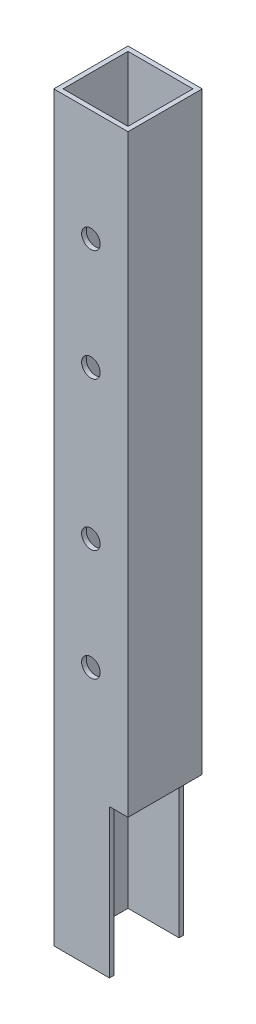
SolidWorks part; units mm, degrees
ref_plane "Front Plane" through (0, 0, 0) normal (0, 0, 1) x (1, 0, 0)
ref_plane "Top Plane" through (0, 0, 0) normal (0, 1, 0) x (1, 0, 0)
ref_plane "Right Plane" through (0, 0, 0) normal (1, 0, 0) x (0, 0, -1)
sketch "Sketch1" plane through (0, 0, 0) normal (0, 1, 0) x (1, 0, 0)
  line L1 (-12.7, 12.7) -> (12.7, 12.7)
  line L2 (-12.7, 12.7) -> (-12.7, -12.7)
  line L3 (-12.7, -12.7) -> (12.7, -12.7)
  line L4 (12.7, 12.7) -> (12.7, -12.7)
  line L5 (-12.7, 12.7) -> (12.7, -12.7) construction
  line L6 (-12.7, -12.7) -> (12.7, 12.7) construction
  line L7 (-11.1125, 11.1125) -> (11.1125, 11.1125)
  line L8 (-11.1125, 11.1125) -> (-11.1125, -11.1125)
  line L9 (-11.1125, -11.1125) -> (11.1125, -11.1125)
  line L10 (11.1125, 11.1125) -> (11.1125, -11.1125)
  line L11 (-11.1125, 11.1125) -> (11.1125, -11.1125) construction
  line L12 (-11.1125, -11.1125) -> (11.1125, 11.1125) construction
  point P0 (0, 0)
  point P6 (0, 0)
  dimension "D1" = 25.4
  dimension "D2" = 25.4
  dimension "D3" = 22.225
  dimension "D4" = 22.225
extrude "Boss-Extrude1" add sketch "Sketch1" along normal mid plane 203.2
sketch "Sketch4" plane through (0, 0, 12.7) normal (0, 0, 1) x (1, 0, 0)
  line L0 (-12.7, 101.6) -> (12.7, 101.6) construction
  line L1 (-12.7, -101.6) -> (12.7, -101.6) construction
  line L2 (12.7, 101.6) -> (12.7, -101.6) construction
  line L3 (-12.7, 101.6) -> (-12.7, -101.6) construction
  circle A0 centre (0, 63.5) radius 3.175
  circle A1 centre (0, -63.5) radius 3.175
  dimension "D1" = 38.1
  dimension "D2" = 38.1
  dimension "D3" = 6.35
  dimension "D4" = 12.7
  dimension "D5" = 12.7
extrude "Cut-Extrude3" cut sketch "Sketch4" against normal blind 25.4
sketch "Sketch5" plane through (0, 0, 12.7) normal (0, 0, 1) x (1, 0, 0)
  line L0 (-12.7, 101.6) -> (-12.7, -101.6) construction
  line L1 (-12.7, 101.6) -> (12.7, 101.6) construction
  line L2 (-12.7, -101.6) -> (12.7, -101.6) construction
  circle A0 centre (0, 25.4) radius 3.175
  circle A1 centre (0, -25.4) radius 3.175
  dimension "D1" = 6.35
  dimension "D2" = 12.7
  dimension "D3" = 12.7
  dimension "D4" = 76.2
  dimension "D5" = 76.2
extrude "Cut-Extrude4" cut sketch "Sketch5" against normal blind 25.4
sketch "Sketch6" plane through (0, -101.6, 0) normal (0, -1, 0) x (1, 0, 0)
  line L0 (6.35, -1000) -> (6.35, 49000) construction
  line L1 (11.1125, -11.1125) -> (-11.1125, -11.1125) construction
  line L2 (12.7, -12.7) -> (-12.7, -12.7) construction
  line L3 (-12.7, -12.7) -> (-12.7, 12.7) construction
  line L4 (-11.1125, -11.1125) -> (-11.1125, 11.1125) construction
  line L5 (-11.1125, 11.1125) -> (11.1125, 11.1125) construction
  line L6 (-12.7, 12.7) -> (12.7, 12.7) construction
  line L7 (6.35, -11.1125) -> (-11.1125, -11.1125)
  line L8 (6.35, -12.7) -> (-12.7, -12.7)
  line L9 (-12.7, -12.7) -> (-12.7, 12.7)
  line L10 (-11.1125, -11.1125) -> (-11.1125, 11.1125)
  line L11 (-11.1125, 11.1125) -> (6.35, 11.1125)
  line L12 (-12.7, 12.7) -> (6.35, 12.7)
  line L13 (6.35, 11.1125) -> (6.35, 12.7)
  line L14 (6.35, -12.7) -> (6.35, -11.1125)
  line L15 (12.7, 12.7) -> (12.7, -12.7) construction
  dimension "D1" = 6.35
extrude "Boss-Extrude2" add sketch "Sketch6" along normal blind 50.8
